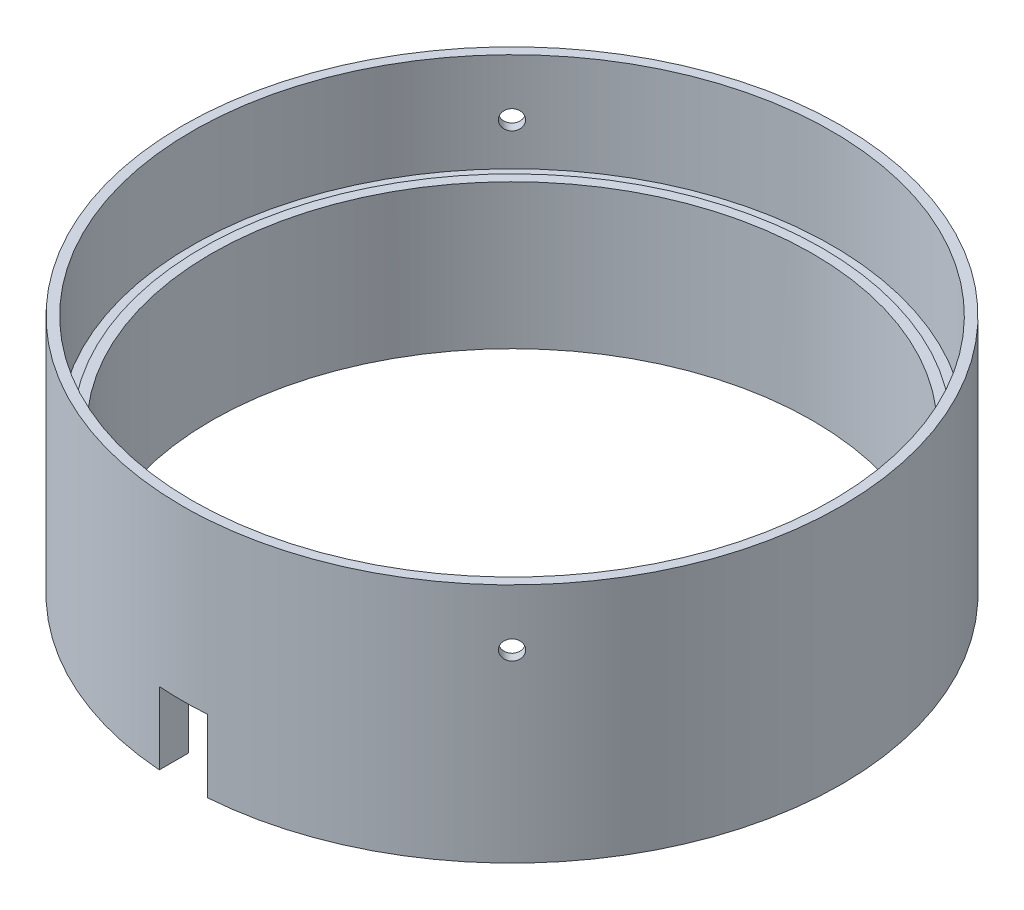
SolidWorks part; units mm, degrees
material "6061 Alloy"
ref_plane "Front Plane" through (0, 0, 0) normal (0, 0, 1) x (1, 0, 0)
ref_plane "Top Plane" through (0, 0, 0) normal (0, 1, 0) x (1, 0, 0)
ref_plane "Right Plane" through (0, 0, 0) normal (1, 0, 0) x (0, 0, -1)
sketch "Sketch1" plane through (0, 0, 0) normal (0, 1, 0) x (-0.9986, 0, -0.0535)
  circle A1 centre (29.226, -15.8776) radius 62.37
  circle A2 centre (29.226, -15.8776) radius 68.37
  dimension "D1" = 6
extrude "Boss-Extrude1" add sketch "Sketch1" along normal blind 30
extrude "Cut-Extrude7" [suppressed] cut sketch "Sketch10" against normal through all
sketch "Sketch10" [suppressed] plane through (19.5625, 5.3, -2.0536) normal (0, 1, 0) x (1, 0, 0)
  line L0 (-50.8712, -5.1997) -> (-48.874, -5.3068) construction
  line L2 (1.24, -7.9941) -> (3.2371, -8.1012) construction
  circle A0 centre (-50.8712, -5.1997) radius 2
  circle A2 centre (-25.2678, -33.7046) radius 2
  circle A3 centre (3.2371, -8.1012) radius 2
  circle A4 centre (-22.3663, 20.4037) radius 2
sketch "Sketch68" plane through (0, 30, 0) normal (0, 1, 0) x (1, 0, 0)
  circle A0 centre (-28.3339, 17.4197) radius 68.37
  circle A1 centre (-28.3339, 17.4197) radius 66.37
  dimension "D1" = 2
extrude "Boss-Extrude2" add sketch "Sketch68" along normal blind 20
sketch "Sketch69" plane through (0, 30, 0) normal (0, 1, 0) x (1, 0, 0)
  circle A0 centre (-28.3339, 17.4197) radius 66.37
  circle A1 centre (-28.3339, 17.4197) radius 64.37
  dimension "D1" = 2
extrude "Cut-Extrude8" cut sketch "Sketch69" against normal blind 0.5
fillet "Fillet1" [suppressed] radius 0.5
sketch "Sketch70" plane through (0, 50, 0) normal (0, 1, 0) x (1, 0, 0)
  line L0 (-96.7039, 17.4197) -> (40.0361, 17.4197) construction
  circle A0 centre (-28.3339, 17.4197) radius 68.37 construction
sketch "Sketch71" plane through (0, 0, 0) normal (0, -1, 0) x (1, 0, 0)
  line L0 (-96.7039, -17.4197) -> (40.0361, -17.4197) construction
ref_plane "Plane1" through (0, 0, -17.4197) normal (0, 0, -1) x (-1, 0, 0)
sketch "Sketch72" plane through (0, 0, -17.4197) normal (0, 0, -1) x (-1, 0, 0)
  line L0 (28.3339, 0) -> (28.3339, 15) construction
  line L1 (96.7039, 0) -> (-40.0361, 0) construction
  line L2 (33.3339, 15) -> (23.3339, 15)
  line L3 (23.3339, 15) -> (23.3339, 0)
  line L4 (23.3339, 0) -> (33.3339, 0)
  line L5 (33.3339, 15) -> (33.3339, 0)
  dimension "D1" = 15
  dimension "D2" = 5
extrude "Cut-Extrude9" cut sketch "Sketch72" against normal through all
extrude "Cut-Extrude12" cut sketch "Sketch75" along normal through all and the other way through all
sketch "Sketch75" plane through (-27.9264, 72.8999, -17.0124) normal (-0.707, 0, 0.7072) x (0.7072, 0, 0.707)
  line L0 (-0.5762, 87.5501) -> (-0.5762, -34.5999) construction
  circle A0 centre (-0.5762, 87.5501) radius 2
  circle A1 centre (-0.5762, -34.5999) radius 2
extrude "Cut-Extrude13" cut sketch "Sketch76" against normal through all and the other way through all
sketch "Sketch76" plane through (-32.7436, 72.8999, -13.0091) normal (0.7072, 0, 0.707) x (0.707, 0, -0.7072)
  line L0 (6.237, -34.5999) -> (6.237, 87.5501) construction
  circle A0 centre (6.237, 87.5501) radius 2
  circle A1 centre (6.237, -34.5999) radius 2
